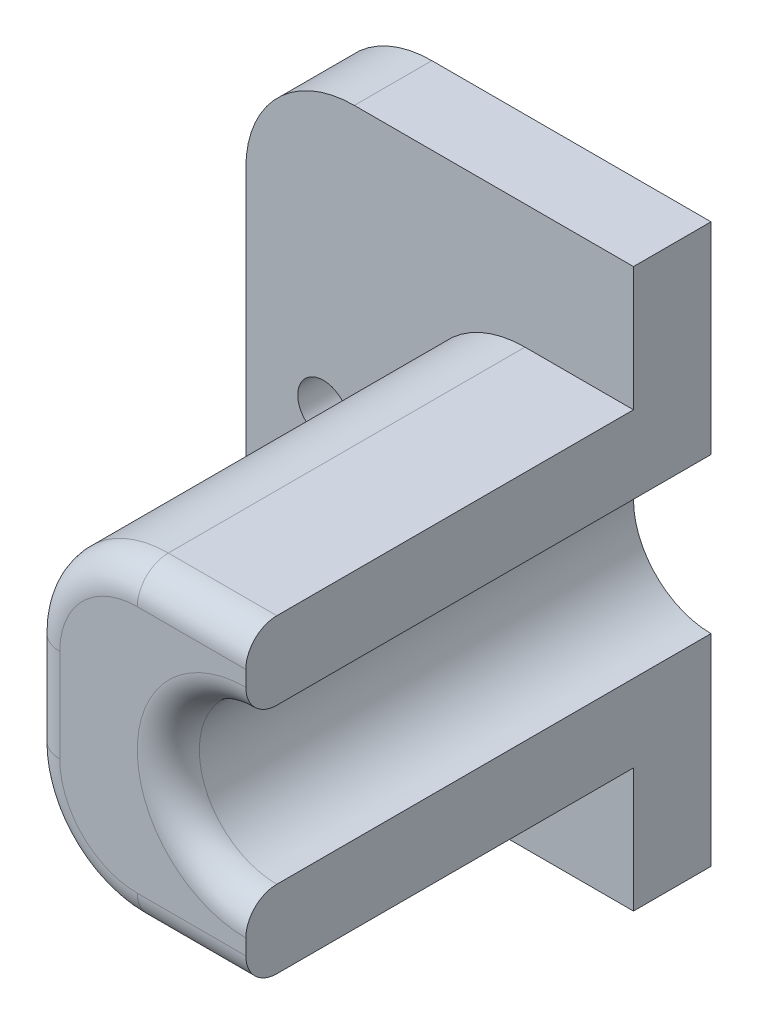
SolidWorks part; units mm, degrees
ref_plane "正面" through (0, 0, 0) normal (0, 0, 1) x (1, 0, 0)
ref_plane "平面" through (0, 0, 0) normal (0, 1, 0) x (1, 0, 0)
ref_plane "右側面" through (0, 0, 0) normal (1, 0, 0) x (0, 0, -1)
sketch "ｽｹｯﾁ1" plane through (0, 0, 0) normal (0, 0, 1) x (1, 0, 0)
  line L0 (0, 0) -> (125.9253, 0) construction
  line L1 (-25, 18) -> (0, 18)
  line L2 (-25, 18) -> (-25, -18)
  line L3 (-25, -18) -> (0, -18)
  line L4 (0, 18) -> (0, -18)
  line L5 (0, 0) -> (0, 68.2499) construction
  circle A0 centre (-20, 0) radius 1.65
  dimension "D4" = 3.3
  dimension "D1" = 0
  dimension "D2" = 25
  dimension "D3" = 18
  dimension "D5" = 20
extrude "ﾎﾞｽ - 押し出し1" add sketch "ｽｹｯﾁ1" along normal blind 5
sketch "ｽｹｯﾁ2" plane through (0, 0, 5) normal (0, 0, 1) x (1, 0, 0)
  line L0 (0, -18) -> (0, 18) construction
  line L1 (-14, 10) -> (0, 10)
  line L2 (-14, 10) -> (-14, -10)
  line L3 (-14, -10) -> (0, -10)
  line L4 (0, 10) -> (0, -10)
  line L5 (0, 0) -> (12.832, 0) construction
  dimension "D1" = 20
  dimension "D2" = 14
extrude "ﾎﾞｽ - 押し出し2" add sketch "ｽｹｯﾁ2" along normal blind 25
sketch "ｽｹｯﾁ3" plane through (0, 0, 30) normal (0, 0, 1) x (1, 0, 0)
  line L0 (0, -10) -> (0, 10) construction
  circle A0 centre (0, 0) radius 5
  dimension "D1" = 10
extrude "ｶｯﾄ - 押し出し1" cut sketch "ｽｹｯﾁ3" against normal blind 35
fillet "ﾌｨﾚｯﾄ1" radius 7 1 edges at (-14, 10, 17.5)
fillet "ﾌｨﾚｯﾄ2" radius 7 1 edges at (-14, -10, 17.5)
fillet "ﾌｨﾚｯﾄ3" radius 7 1 edges at (-25, 18, 2.5)
fillet "ﾌｨﾚｯﾄ4" radius 7 1 edges at (-25, -18, 2.5)
fillet "ﾌｨﾚｯﾄ5" radius 2 6 edges at (-5, 0, 30) (-3.5, 10, 30) (-11.9497, 7.9497, 30) (-14, 0, 30) (-11.9497, -7.9497, 30) (-3.5, -10, 30)
